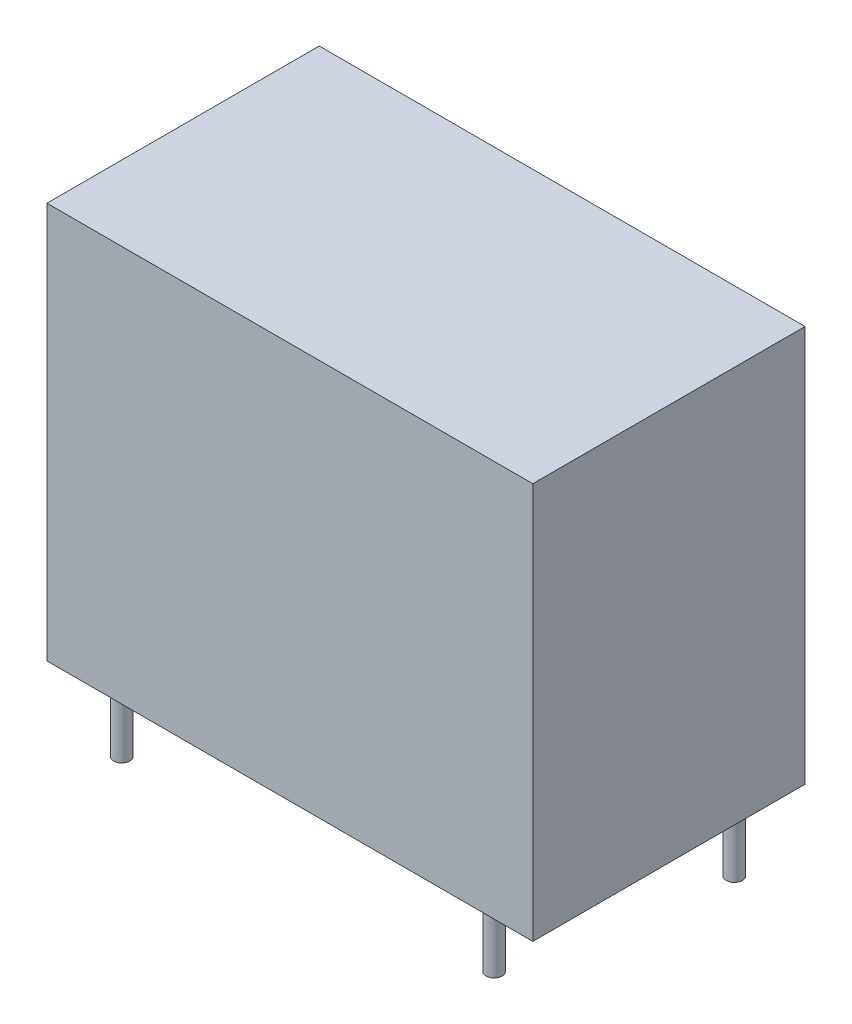
SolidWorks part; units mm, degrees
material "ABS"
ref_plane "Спереди" through (0, 0, 0) normal (0, 0, 1) x (1, 0, 0)
ref_plane "Сверху" through (0, 0, 0) normal (0, 1, 0) x (1, 0, 0)
ref_plane "Справа" through (0, 0, 0) normal (1, 0, 0) x (0, 0, -1)
sketch "Эскиз1" plane through (0, 0, 0) normal (0, 1, 0) x (1, 0, 0)
  line L1 (-9.1, 5.1) -> (9.1, 5.1)
  line L2 (-9.1, 5.1) -> (-9.1, -5.1)
  line L3 (-9.1, -5.1) -> (9.1, -5.1)
  line L4 (9.1, 5.1) -> (9.1, -5.1)
extrude "Бобышка-Вытянуть1" add sketch "Эскиз1" along normal blind 14.85
sketch "Эскиз3" plane through (0, 0, 0) normal (0, -1, 0) x (1, 0, 0)
  circle A0 centre (-7.6, 3.8) radius 0.3
  circle A1 centre (-7.6, -3.8) radius 0.3
  circle A2 centre (6.35, 3.8) radius 0.3
  circle A3 centre (4.95, -3.8) radius 0.3
  circle A4 centre (7.75, -3.8) radius 0.3
extrude "Бобышка-Вытянуть2" add sketch "Эскиз3" along normal blind 3
